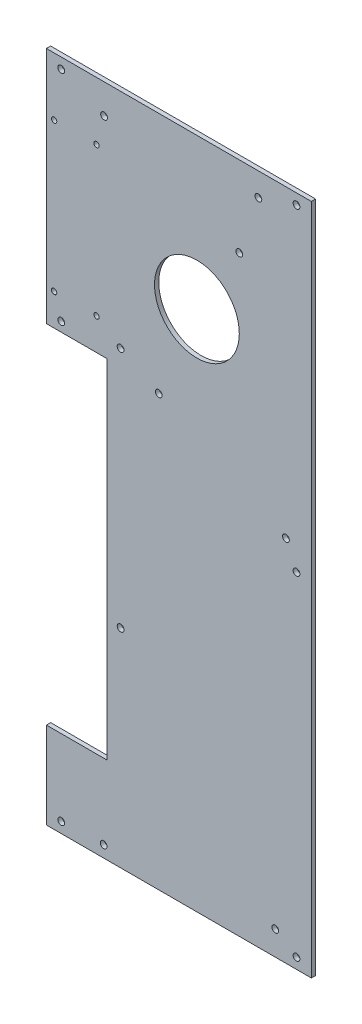
SolidWorks part; units mm, degrees
ref_plane "Front Plane" through (0, 0, 0) normal (1, 0, 0) x (0, 1, 0)
ref_plane "Top Plane" through (0, 0, 0) normal (0, 0, 1) x (0, 1, 0)
ref_plane "Right Plane" through (0, 0, 0) normal (0, 1, 0) x (-1, 0, 0)
sketch "Sketch1" plane through (0, 0, 0) normal (0, 0, 1) x (0, 1, 0)
  line L0 (-57.15, 6.35) -> (-57.15, 35)
  line L1 (-98, 6.35) -> (219.3, 6.35)
  line L2 (-98, 6.35) -> (-98, -90)
  line L3 (-98, -90) -> (219.3, -90)
  line L4 (219.3, 6.35) -> (219.3, -90)
  line L5 (-57.15, 35) -> (-98, 35)
  line L6 (-98, 35) -> (-98, 6.35)
  line L7 (196.85, 6.35) -> (196.85, 35)
  line L8 (196.85, 35) -> (219.3, 35)
  line L9 (219.3, 35) -> (219.3, 6.35)
  line L10 (196.85, 35) -> (106.85, 35)
  line L11 (121.85, 31.35) -> (191.85, 31.35) construction
  line L12 (121.85, 31.35) -> (121.85, 11.35) construction
  line L13 (121.85, 11.35) -> (191.85, 11.35) construction
  line L14 (191.85, 31.35) -> (191.85, 11.35) construction
  line L15 (106.85, 35) -> (106.85, 6.35)
  circle A0 centre (-86.5, -73) radius 1.6
  circle A1 centre (-92.5, 8) radius 1.6
  circle A2 centre (0, 0) radius 1.6
  circle A3 centre (114.3, 0) radius 1.6
  circle A4 centre (104.8, -18) radius 1.6
  circle A5 centre (181.3, -56) radius 1.6
  circle A6 centre (208.3, -65) radius 1.6
  circle A7 centre (205.3, 7.8) radius 1.6
  circle A8 centre (75.7, -78) radius 1.6
  circle A18 centre (148.3, -36) radius 20
  circle A19 centre (-93, 28) radius 1.6
  circle A20 centre (-93, -83) radius 1.6
  circle A21 centre (214.3, -83) radius 1.6
  circle A22 centre (214.3, 28) radius 1.6
  circle A23 centre (121.85, 31.35) radius 1.25
  circle A24 centre (121.85, 11.35) radius 1.25
  circle A25 centre (191.85, 11.35) radius 1.25
  circle A26 centre (191.85, 31.35) radius 1.25
  circle A27 centre (111.3, 28) radius 1.6
  circle A28 centre (64.3, -83) radius 1.6
  dimension "D1" = 3.2
  dimension "D13" = 78
  dimension "D23" = 3.2
  dimension "D26" = 34
  dimension "D27" = 40
  dimension "D29" = 5
  dimension "D34" = 2.5
  dimension "D38" = 103
  dimension "D39" = 150
  dimension "D2" = 114.3
  dimension "D3" = 8
  dimension "D4" = 92.5
  dimension "D5" = 73
  dimension "D6" = 86.5
  dimension "D7" = 98
  dimension "D8" = 105
  dimension "D9" = 91
  dimension "D10" = 7.8
  dimension "D11" = 94
  dimension "D12" = 65
  dimension "D14" = 38.6
  dimension "D15" = 9.5
  dimension "D16" = 18
  dimension "D17" = 67
  dimension "D18" = 56
  dimension "D19" = 90
  dimension "D20" = 6.35
  dimension "D21" = 57.15
  dimension "D22" = 35
  dimension "D24" = 7
  dimension "D25" = 82.55
  dimension "D28" = 36
  dimension "D30" = 7
  dimension "D31" = 5
  dimension "D32" = 20
  dimension "D33" = 70
  dimension "D35" = 5
  dimension "D36" = 5
  dimension "D37" = 15
extrude "Boss-Extrude1" add sketch "Sketch1" against normal blind 2 contours A7 L1 L2 L3 L4 A21 A20 A18 A8 A6 A5 A4 A3 A2 A0 | L5 L6 L1 L0 A19 A1 | A7 L1 L9 L8 L7 A22 | L10 L15 L1 L7 A26 A25 A24 A23
